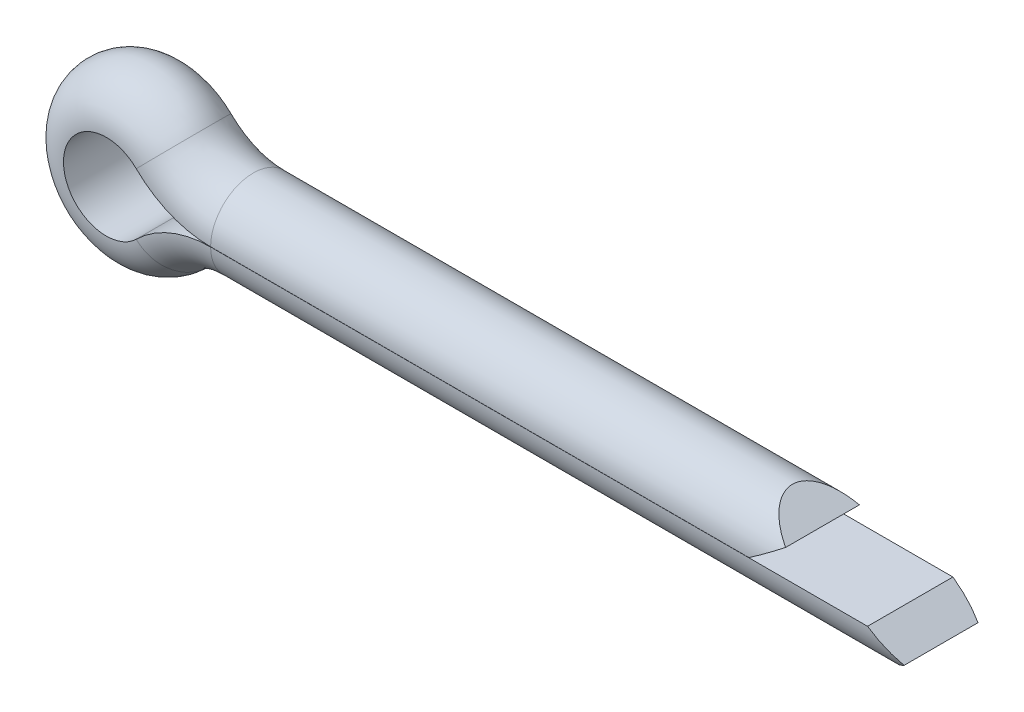
SolidWorks part; units mm, degrees
ref_plane "Front" through (0, 0, 0) normal (0, 0, 1) x (1, 0, 0)
ref_plane "Top" through (0, 0, 0) normal (0, 1, 0) x (1, 0, 0)
ref_plane "Right" through (0, 0, 0) normal (1, 0, 0) x (0, 0, -1)
sketch "PathSke" plane through (0, 0, 0) normal (0, 0, 1) x (1, 0, 0)
  line L0 (12, 0.9) -> (0, 0.9)
  line L1 (0, -0.9) -> (14.5, -0.9)
  line L2 (0, 0) -> (49.7718, 0) construction
  line L3 (0, 0) -> (0, 16.5256) construction
  line L4 (-4, 0) -> (-4, 12.0776) construction
  arc A0 (0, 0.9) -> (-0.9384, 1.2839) centre (0, 2.2389) cw
  arc A1 (-0.9384, 1.2839) -> (-0.9384, -1.2839) centre (-2.2, 0) ccw
  arc A2 (-0.9384, -1.2839) -> (0, -0.9) centre (0, -2.2389) cw
  dimension "Diameter" = 1.8
  dimension "Head_dia" = 3.6
  dimension "Head_ht" = 4
  dimension "Length" = 12
  dimension "Tip_offset" = 2.5
ref_plane "SectionPlane" through (12, 0, 0) normal (1, 0, 0) x (0, 0, -1)
sketch "SectionSke" plane through (12, 0, 0) normal (1, 0, 0) x (0, 0, -1)
  line L1 (-0.9, 0.002) -> (0.9, 0.002)
  arc A0 (0.9, 0.002) -> (-0.9, 0.002) centre (0, 0) ccw
  dimension "Diameter" = 1.8
  dimension "D1" = 0.002
sweep "Body" add profiles "SectionSke" path "PathSke"
sketch "ConeCutSke" plane through (0, 0, 0) normal (0, 0, 1) x (1, 0, 0)
  line L0 (0, 0) -> (0, 16.2682) construction
  line L1 (0, 0) -> (75.9079, 0) construction
  line L2 (0, 0) -> (14.5, 0) construction
  line L3 (12, 0.451) -> (11.353, 0.91)
  line L4 (12, 0.002) -> (12, 0.9) construction
  line L6 (12, 0.451) -> (11.3474, 0)
  line L7 (14.5, -0.451) -> (13.8474, 0)
  line L8 (14.5, -0.9) -> (14.5, -0.002) construction
  line L9 (14.5, -0.451) -> (13.853, -0.91)
  line L10 (13.8474, 0) -> (11.3474, 0)
  line L11 (11.353, 0.91) -> (14.51, 0.91)
  line L12 (14.51, 0.91) -> (14.51, -0.91)
  line L13 (14.51, -0.91) -> (13.853, -0.91)
  line L14 (12, 0.9) -> (0, 0.9) construction
  dimension "D1" = 0.01
  dimension "D2" = 0.01
  dimension "D3" = 70
  dimension "D4" = 70
extrude "ConeCut" cut sketch "ConeCutSke" against normal through all and the other way through all
equation "' \"Diameter@PathSke\" = 9.5"
equation "' \"Head_dia@PathSke\" = 19"
equation "' \"Head_ht@PathSke\" = 20"
equation "' \"Tip_offset@PathSke\" = 6.3"
equation "' \"Length@PathSke\" = 45"
equation "' \"Diameter@PathSke\" = 1"
equation "' \"Head_dia@PathSke\" = 2"
equation "' \"Head_ht@PathSke\" = 3"
equation "' \"Tip_offset@PathSke\" = 2.5"
equation "' \"Length@PathSke\" = 8"
equation "' \"Diameter@PathSke\" = 0.5"
equation "' \"Head_dia@PathSke\" = 1"
equation "' \"Head_ht@PathSke\" = 2"
equation "' \"Tip_offset@PathSke\" = 1.6"
equation "' \"Length@PathSke\" = 4"
equation "\"Diameter@SectionSke\" = \"Diameter@PathSke\""
equation "\"Length@SectionPlane\" = \"Length@PathSke\""
